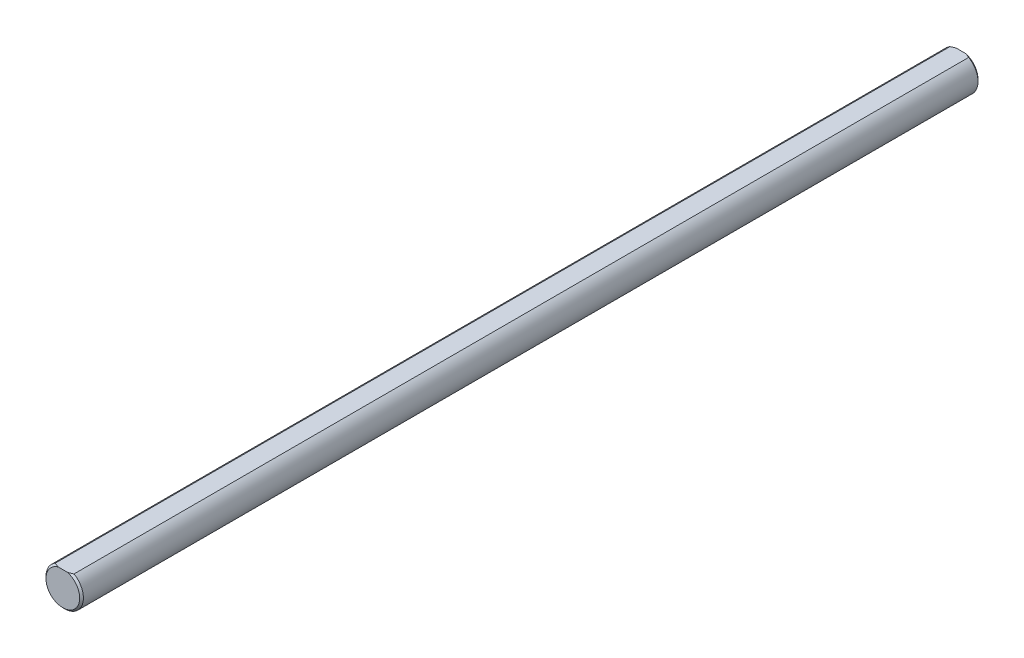
SolidWorks part; units mm, degrees
material "AISI 1045 Steel, cold drawn"
ref_plane "Front Plane" through (0, 0, 0) normal (0, 0, 1) x (1, 0, 0)
ref_plane "Top Plane" through (0, 0, 0) normal (0, 1, 0) x (1, 0, 0)
ref_plane "Right Plane" through (0, 0, 0) normal (1, 0, 0) x (0, 0, -1)
sketch "Sketch1" plane through (0, 0, 0) normal (0, 0, 1) x (1, 0, 0)
  circle A1 centre (0, 0) radius 6.35 construction
  dimension "Diameter" = 12.7
sketch "Sketch2" plane through (0, 0, 0) normal (1, 0, 0) x (0, 0, -1)
  line L0 (-152.4, 6.35) -> (152.4, 6.35) construction
  line L1 (0, 6.35) -> (0, -6.35) construction
  line L2 (0, 6.35) -> (0, -6.35) construction
  point P2 (0, 6.35)
  point P3 (127, 6.35)
  point P4 (-127, 6.35)
  dimension "Length" = 304.8
  dimension "D2" = 25.4
  dimension "D1" = 25.4
sketch "Sketch3" plane through (0, 0, 0) normal (0, 0, 1) x (1, 0, 0)
  circle A1 centre (0, 0) radius 6.35 construction
  circle A3 centre (0, 0) radius 6.35
extrude "Boss-Extrude2" add sketch "Sketch3" along normal up to vertex (152.4 mm away) and the other way up to vertex (152.4 mm away) up to point (0, 6.35, 152.4) other way up to point (0, 6.35, -152.4)
sketch "Sketch10" plane through (0, 0, 0) normal (0, 0, 1) x (1, 0, 0)
  line L0 (-3.175, 5.4993) -> (3.175, 5.4993)
  line L1 (0, 0) -> (0, 6.35) construction
  circle A0 centre (0, 0) radius 6.35 construction
  circle A1 centre (0, 0) radius 6.35 construction
  arc A2 (-3.175, 5.4993) -> (3.175, 5.4993) centre (0, 0) cw
extrude "Cut-Extrude5" cut sketch "Sketch10" against normal through all both and the other way through all
chamfer "Chamfer1" distance 0.635 angle 45 4 edges at (0, -6.35, 152.4) (0, -6.35, -152.4) (0, 5.4993, -152.4) (0, 5.4993, 152.4)
equation "\"D1@Chamfer1\"= \"Diameter@Sketch1\" / 20"
equation "\"D1@Sketch2\"=\"Diameter@Sketch1\"*2"
equation "\"D2@Sketch2\"=\"D1@Sketch2\""
